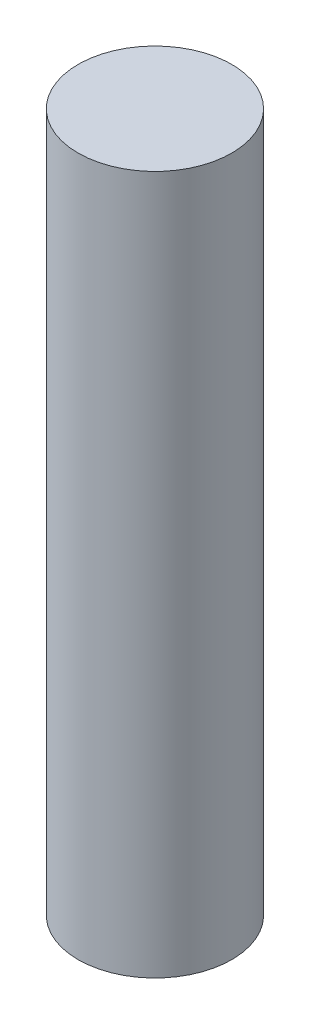
SolidWorks part; units mm, degrees
material "PBT General Purpose"
ref_plane "Front Plane" through (0, 0, 0) normal (0, 0, 1) x (1, 0, 0)
ref_plane "Top Plane" through (0, 0, 0) normal (0, 1, 0) x (1, 0, 0)
ref_plane "Right Plane" through (0, 0, 0) normal (1, 0, 0) x (0, 0, -1)
sketch "Sketch1" plane through (0, 0, 0) normal (0, 1, 0) x (1, 0, 0)
  circle A0 centre (0, 0) radius 27.5
extrude "Boss-Extrude1" add sketch "Sketch1" along normal blind 250
